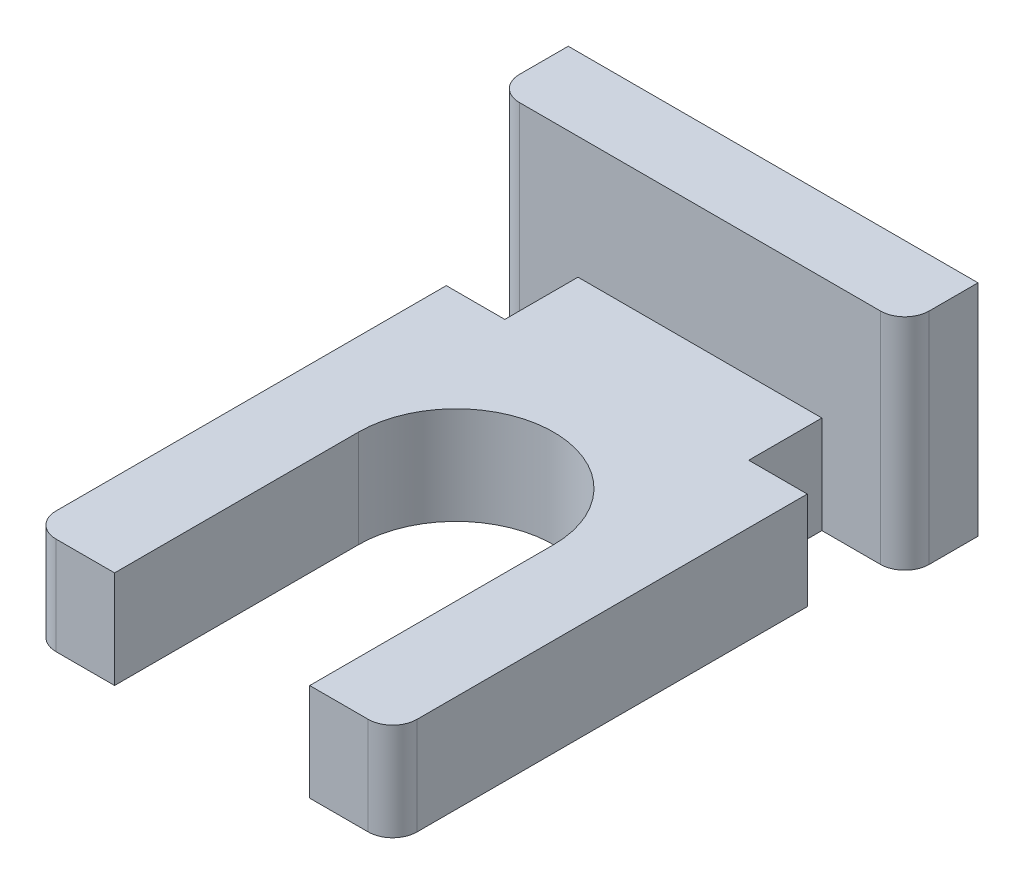
SolidWorks part; units mm, degrees
ref_plane "Plan de face" through (0, 0, 0) normal (0, 0, 1) x (1, 0, 0)
ref_plane "Plan de dessus" through (0, 0, 0) normal (0, 1, 0) x (1, 0, 0)
ref_plane "Plan de droite" through (0, 0, 0) normal (1, 0, 0) x (0, 0, -1)
sketch "Esquisse1" plane through (0, 0, 0) normal (0, 0, 1) x (1, 0, 0)
  line L1 (-42, -22.5) -> (42, -22.5)
  line L2 (-42, -22.5) -> (-42, 22.5)
  line L3 (-42, 22.5) -> (42, 22.5)
  line L4 (42, -22.5) -> (42, 22.5)
  line L5 (-42, -22.5) -> (42, 22.5) construction
  line L6 (-42, 22.5) -> (42, -22.5) construction
  point P0 (0, 0)
  dimension "D1" = 84
  dimension "D2" = 45
extrude "Boss.-Extru.1" add sketch "Esquisse1" along normal blind 15 contours L3 L4 L1 L2
sketch "Esquisse2" plane through (0, -22.5, 0) normal (0, -1, 0) x (1, 0, 0)
  line L1 (37, 115) -> (37, 30)
  line L12 (37, 30) -> (25, 30)
  line L13 (0, 15) -> (-25, 15)
  line L14 (-42, 15) -> (42, 15) construction
  line L15 (-25, 15) -> (-25, 30)
  line L16 (-25, 30) -> (-37, 30)
  line L17 (-37, 30) -> (-37, 115)
  line L18 (-37, 115) -> (-20, 115)
  line L19 (-20, 115) -> (-20, 65)
  line L20 (20, 65) -> (20, 115)
  line L21 (20, 115) -> (37, 115)
  line L22 (25, 30) -> (25, 15)
  line L23 (25, 15) -> (0, 15)
  line L24 (-42, 0) -> (42, 0) construction
  arc A1 (-20, 65) -> (20, 65) centre (0, 65) ccw
  dimension "D1" = 25
  dimension "D2" = 25
  dimension "D3" = 17
  dimension "D4" = 17
  dimension "D5" = 40
  dimension "D6" = 115
  dimension "D7" = 115
  dimension "D8" = 30
  dimension "D9" = 30
  dimension "D10" = 12
  dimension "D11" = 65
extrude "Boss.-Extru.2" add sketch "Esquisse2" against normal blind 20 contours A1 L20 L21 L1 L12 L22 L23 L13 L15 L16 L17 L18 L19
fillet "Congé1" radius 5 4 edges at (42, 0, 15) (-42, 0, 15) (-37, -12.5, 115) (37, -12.5, 115)
